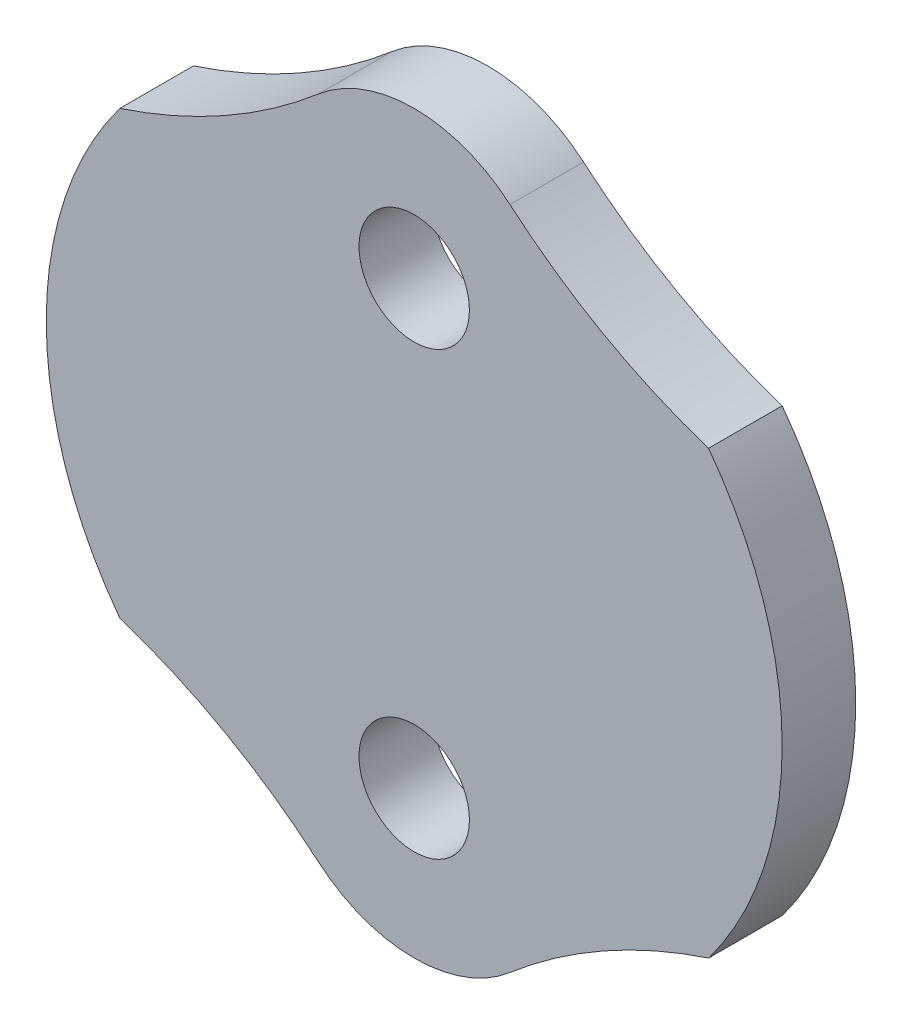
SolidWorks part; units mm, degrees
ref_plane "Front Plane" through (0, 0, 0) normal (0, 0, 1) x (1, 0, 0)
ref_plane "Top Plane" through (0, 0, 0) normal (0, 1, 0) x (1, 0, 0)
ref_plane "Right Plane" through (0, 0, 0) normal (1, 0, 0) x (0, 0, -1)
sketch "Sketch1" plane through (0, 0, 0) normal (0, 0, 1) x (1, 0, 0)
  circle A0 centre (0, 0) radius 2.3813
  circle A1 centre (0, 19.05) radius 2.3813
  circle A2 centre (0, 9.525) radius 15.875
  dimension "D1" = 19.05
  dimension "D2" = 4.7625
  dimension "D3" = 4.7625
  dimension "D5" = 31.75
  dimension "D4" = 9.525
extrude "Boss-Extrude2" add sketch "Sketch1" along normal blind 3.175 contours A2
sketch "Sketch2" plane through (0, 0, 3.175) normal (0, 0, 1) x (1, 0, 0)
  line L0 (0, 9.525) -> (-4.1303, 9.525)
  line L1 (-12.7, 19.05) -> (12.7, 19.05)
  line L2 (-12.7, 19.05) -> (-12.7, 0)
  line L3 (-12.7, 0) -> (12.7, 0)
  line L4 (12.7, 19.05) -> (12.7, 0)
  line L5 (0, 9.525) -> (0, 11.6054)
  circle A0 centre (0, 19.05) radius 6.35
  circle A1 centre (0, 0) radius 6.35
  circle A2 centre (0, 9.525) radius 15.875 construction
  arc A3 (-12.7, 19.05) -> (-4.1303, 23.8732) centre (-20.5918, 43.0967) ccw
  arc A4 (12.7, 19.05) -> (4.1303, 23.8732) centre (20.5918, 43.0967) cw
  arc A5 (12.7, 0) -> (4.1303, -4.8232) centre (20.5918, -24.0467) ccw
  arc A6 (-12.7, 0) -> (-4.1303, -4.8232) centre (-20.5918, -24.0467) cw
  circle A7 centre (0, 9.525) radius 26.6859
  circle A8 centre (0, 9.525) radius 15.875
  circle M6 centre (0, 9.525) radius 15.875
extrude "Cut-Extrude1" cut sketch "Sketch2" against normal through all contours A3 A0 M6 | A7 M6 | A4 A0 M6 | A5 A1 M6 | A6 A1 M6
